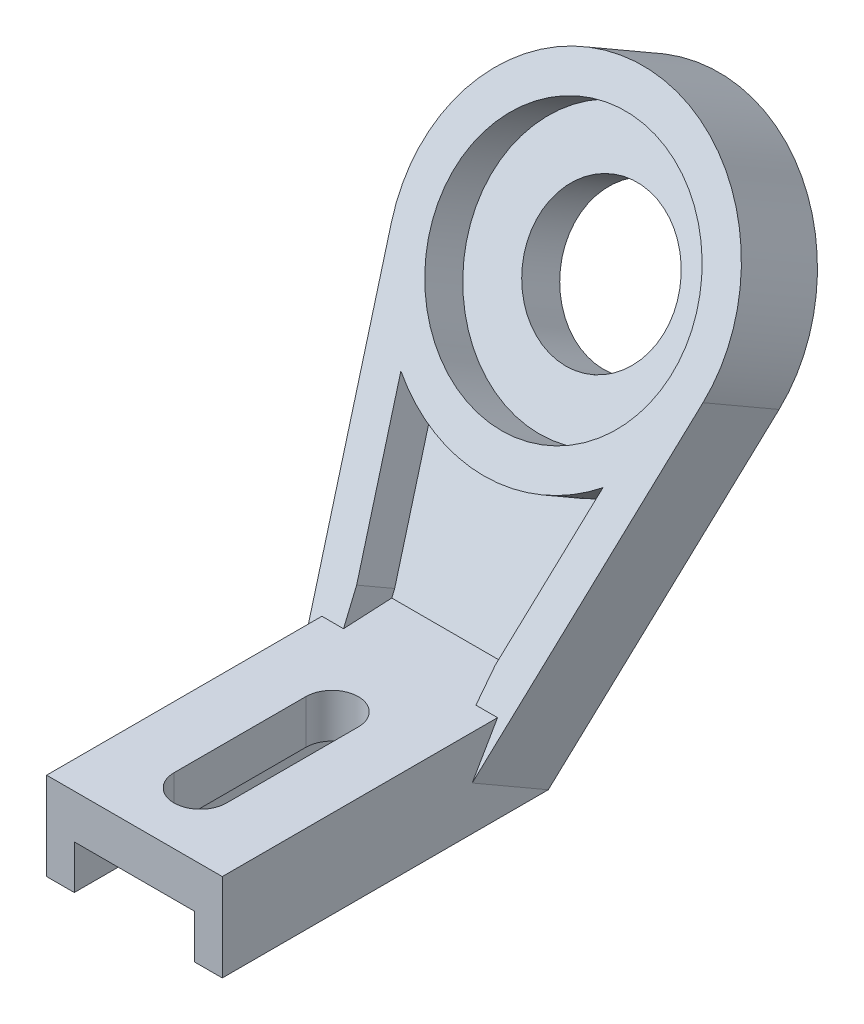
SolidWorks part; units mm, degrees
ref_plane "Front Plane" through (0, 0, 0) normal (0, 0, 1) x (1, 0, 0)
ref_plane "Top Plane" through (0, 0, 0) normal (0, 1, 0) x (1, 0, 0)
ref_plane "Right Plane" through (0, 0, 0) normal (1, 0, 0) x (0, 0, -1)
sketch "Sketch1" plane through (0, 0, 0) normal (0, 1, 0) x (1, 0, 0)
  line L0 (0, -729.8591) -> (0, 35763.0938) construction
  line L2 (-6.35, 25.4) -> (6.35, 25.4)
  line L3 (-6.35, 25.4) -> (-6.35, 0)
  line L4 (-6.35, 0) -> (6.35, 0)
  line L5 (6.35, 25.4) -> (6.35, 0)
  point P7 (0, 0)
  dimension "D1" = 25.4
  dimension "D2" = 12.7
extrude "Boss-Extrude1" add sketch "Sketch1" along normal blind 3.175
ref_plane "Plane1" through (0, 10.9985, -6.35) normal (0, 0.866, -0.5) x (-1, 0, 0)
sketch "Sketch17" plane through (0, 10.9985, -6.35) normal (0, 0.866, -0.5) x (-1, 0, 0)
  line L1 (6.35, -21.997) -> (-6.35, -21.997)
  line L2 (6.35, -21.997) -> (6.35, -18.822)
  line L3 (6.35, -18.822) -> (-6.35, -18.822)
  line L4 (-6.35, -21.997) -> (-6.35, -18.822)
  dimension "D1" = 3.175
extrude "Boss-Extrude5" add sketch "Sketch17" along normal blind 31.75
sketch "Sketch21" plane through (0, -9.411, -16.3004) normal (0, 0.5, 0.866) x (1, 0, 0)
  line L0 (-6.35, 14.5331) -> (6.35, 44.45) construction
  line L1 (-6.35, 44.45) -> (6.35, 14.5331) construction
  line L2 (-2.3066, 34.925) -> (2.3066, 34.925) construction
  line L3 (-6.35, 44.45) -> (6.35, 44.45) construction
  point P8 (0, 29.4915)
  dimension "D1" = 9.525
hole_wizard "3/8 Clearance Hole1" positions "Sketch24" profile "Sketch25" hole size "3/8" standard "ANSI Inch" end condition through all
sketch "Sketch24" plane through (0, -9.411, -16.3004) normal (0, 0.5, 0.866) x (1, 0, 0)
  line L0 (-2.3066, 34.925) -> (2.3066, 34.925) construction
  point P0 (0, 34.925)
sketch "Sketch25" plane through (0, 20.8349, -33.7629) normal (1, 0, 0) x (0, -0.866, 0.5)
  line L0 (0, 0) -> (0, 16.9232)
  line L1 (0, 16.9232) -> (5.1587, 16.9232)
  line L2 (5.1587, 16.9232) -> (5.1587, 0)
  line L5 (5.1587, 0) -> (0, 0)
  line L11 (0, -6.35) -> (0, 107.95) construction
  dimension "Thru Hole Dia." = 10.3175
  dimension "Thru Hole Depth" = 16.9232
sketch "Sketch26" plane through (0, -9.411, -16.3004) normal (0, 0.5, 0.866) x (1, 0, 0)
  line L0 (-2.3066, 34.925) -> (2.3066, 34.925) construction
  circle A2 centre (0, 34.925) radius 5.1587 construction
  circle A3 centre (0, 34.925) radius 11.5087
  line M2 (-6.35, 14.5331) -> (6.35, 14.5331)
  line M3 (6.35, 14.5331) -> (6.35, 44.45)
  line M4 (6.35, 44.45) -> (-6.35, 44.45)
  line M5 (-6.35, 44.45) -> (-6.35, 14.5331)
  dimension "D1" = 6.35
extrude "Boss-Extrude6" add sketch "Sketch26" against normal up to surface (3.175 mm away) contours A3 M2 M5 M4 M3
sketch "Sketch27" plane through (0, 3.175, 0) normal (0, 1, 0) x (1, 0, 0)
  line L0 (0, -1000) -> (0, 49000) construction
  line L1 (0, 14.2875) -> (0, 4.7625) construction
  line L2 (1.8987, 14.2875) -> (1.8987, 4.7625)
  line L3 (-1.8986, 14.2875) -> (-1.8986, 4.7625)
  line L4 (-6.35, 0) -> (6.35, 0) construction
  arc A0 (1.8987, 14.2875) -> (-1.8986, 14.2875) centre (0, 14.2875) ccw
  arc A1 (-1.8986, 4.7625) -> (1.8987, 4.7625) centre (0, 4.7625) ccw
  point P5 (0, 9.525)
  dimension "D3" = 3.7973
  dimension "D1" = 4.7625
  dimension "D2" = 9.525
extrude "Cut-Extrude4" cut sketch "Sketch27" against normal through all
sketch "Sketch31" plane through (0, 0, 0) normal (0, -1, 0) x (1, 0, 0)
  line L0 (6.35, -25.4) -> (-6.35, -25.4) construction
  line L1 (-6.35, 0) -> (-4.3498, 0)
  line L2 (-6.35, 0) -> (-6.35, -25.4)
  line L3 (-6.35, -25.4) -> (-4.3498, -25.4)
  line L4 (-4.3498, 0) -> (-4.3498, -25.4)
  line L5 (6.35, 0) -> (4.3498, 0)
  line L6 (6.35, 0) -> (6.35, -25.4)
  line L7 (6.35, -25.4) -> (4.3498, -25.4)
  line L8 (4.3498, 0) -> (4.3498, -25.4)
  line L9 (6.35, -25.4) -> (-6.35, -25.4) construction
  dimension "D1" = 8.6995
extrude "Boss-Extrude9" add sketch "Sketch31" along normal blind 18.034
sketch "Sketch32" plane through (0, 0, 0) normal (1, 0, 0) x (0, 0, -1)
  line L2 (0, -3.175) -> (23.5669, -3.175)
  line L3 (0, 3.175) -> (0, -18.034) construction
  line L5 (23.5669, -3.175) -> (25.4, 0)
  line L6 (25.4, 0) -> (41.0903, -22.9625)
  line L12 (41.0903, -22.9625) -> (-8.9533, -22.6242)
  line L16 (-8.9533, -22.6242) -> (0, -3.175)
  line L19 (0, 3.175) -> (23.5669, 3.175) construction
  line L21 (31.7133, 10.935) -> (25.4, 0) construction
  dimension "D1" = 6.35
extrude "Cut-Extrude6" cut sketch "Sketch32" against normal through all both and the other way through all
sketch "Sketch35" plane through (0, -10.9985, -19.05) normal (0, -0.5, -0.866) x (-1, 0, 0)
  line L0 (-6.35, 9.0338) -> (-11.2657, 32.5723)
  line L1 (6.35, 9.0338) -> (11.2657, 32.5723)
  line L2 (-6.35, 25.3266) -> (-6.35, 9.0338) construction
  line L3 (-6.35, 25.3266) -> (-6.35, 9.0338)
  line L4 (6.35, 25.3266) -> (6.35, 9.0338) construction
  line L5 (6.35, 25.3266) -> (6.35, 9.0338)
  arc A0 (6.35, 25.3266) -> (-6.35, 25.3266) centre (0, 34.925) ccw construction
  arc A1 (6.35, 25.3266) -> (11.2657, 32.5723) centre (0, 34.925) ccw
  arc A2 (-11.2657, 32.5723) -> (-6.35, 25.3266) centre (0, 34.925) ccw
extrude "Boss-Extrude10" add sketch "Sketch35" against normal up to surface (3.175 mm away) up to face at (0, 12.4186, -28.9037)
sketch "Sketch36" plane through (0, -9.411, -16.3004) normal (0, 0.5, 0.866) x (1, 0, 0)
  line L0 (-5.0108, 15.0463) -> (-4.4715, 9.4261)
  line L2 (-6.35, 9.0338) -> (-4.4715, 9.4261)
  line L3 (4.4715, 9.4261) -> (6.35, 9.0338)
  line L4 (3.8636, 9.5531) -> (8.7793, 33.0916)
  line L5 (-8.7793, 33.0916) -> (-3.8636, 9.5531)
  line L6 (5.0108, 15.0463) -> (7.305, 26.0319)
  line L7 (-7.305, 26.0319) -> (-5.0108, 15.0463)
  line L8 (4.4715, 9.4261) -> (5.0108, 15.0463)
  line L11 (-11.2657, 32.5723) -> (-6.35, 9.0338)
  line L12 (-6.35, 9.0338) -> (-6.35, 14.5331)
  line L13 (-6.35, 14.5331) -> (6.35, 14.5331)
  line L14 (6.35, 14.5331) -> (6.35, 9.0338)
  line L15 (6.35, 9.0338) -> (11.2657, 32.5723)
  line L16 (-11.2657, 32.5723) -> (-6.35, 9.0338)
  line L20 (6.35, 9.0338) -> (11.2657, 32.5723)
  arc A0 (-8.7793, 33.0916) -> (8.7793, 33.0916) centre (0, 34.925) ccw
  arc A2 (8.7793, 33.0916) -> (-8.7793, 33.0916) centre (0, 34.925) ccw
  arc A3 (8.7793, 33.0916) -> (-8.7793, 33.0916) centre (0, 34.925) ccw
  arc A4 (11.2657, 32.5723) -> (-11.2657, 32.5723) centre (0, 34.925) ccw
  arc A5 (11.2657, 32.5723) -> (-11.2657, 32.5723) centre (0, 34.925) ccw
  arc A6 (-7.305, 26.0319) -> (7.305, 26.0319) centre (0, 34.925) ccw
  arc A7 (-11.2657, 32.5723) -> (11.2657, 32.5723) centre (0, 34.925) ccw construction
  dimension "D3" = 2.54
  dimension "D1" = 2.54
  dimension "D2" = 0
extrude "Boss-Extrude11" add sketch "Sketch36" along normal blind 3.175
